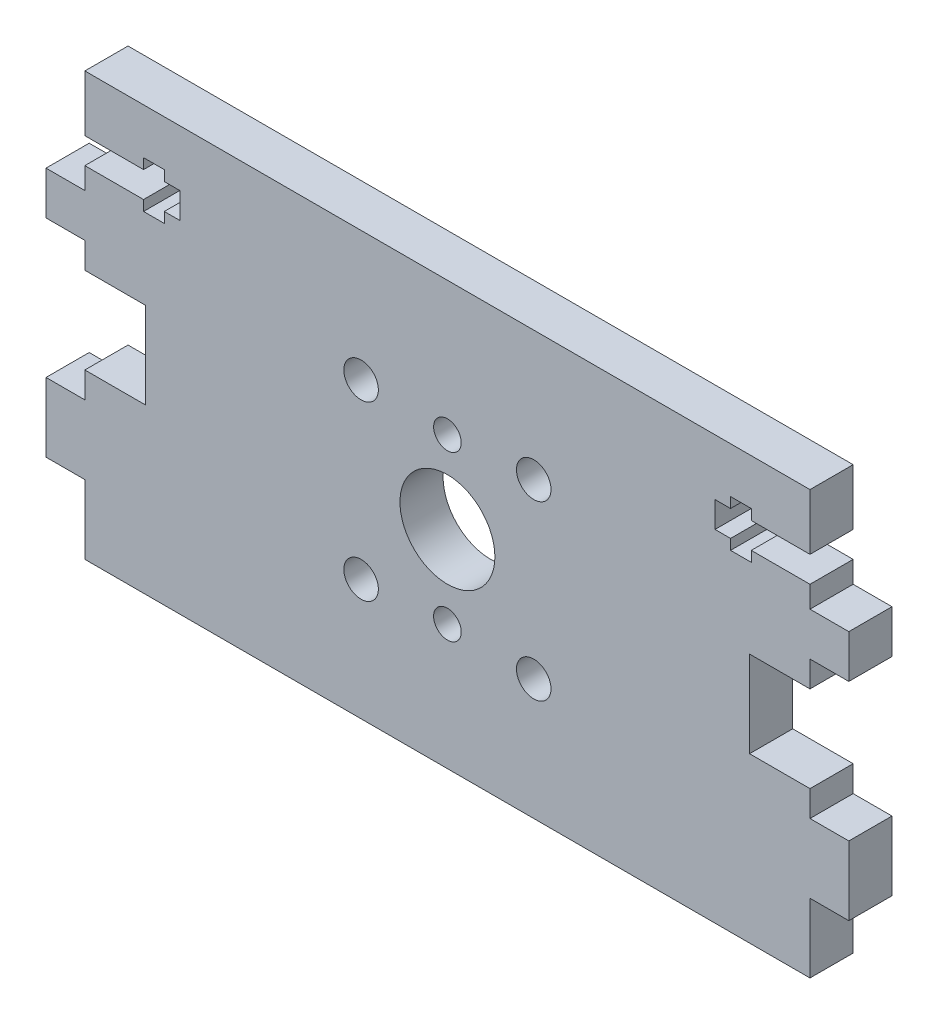
SolidWorks part; units mm, degrees
ref_plane "Plano frontal" through (0, 0, 0) normal (0, 0, 1) x (1, 0, 0)
ref_plane "Plano superior" through (0, 0, 0) normal (0, 1, 0) x (1, 0, 0)
ref_plane "Plano direito" through (0, 0, 0) normal (1, 0, 0) x (0, 0, -1)
sketch "Model" plane through (0, 0, 0) normal (0, 0, 1) x (1, 0, 0)
  line L0 (-6.2, 114.7) -> (-6.2, 113.5)
  line L1 (-6.2, 113.5) -> (-8, 113.5)
  line L2 (-8, 113.5) -> (-8, 110.5)
  line L3 (-8, 110.5) -> (-6.2, 110.5)
  line L4 (-6.2, 110.5) -> (-6.2, 109.3)
  line L5 (-6.2, 109.3) -> (-3.8, 109.3)
  line L6 (-3.8, 109.3) -> (-3.8, 110.5)
  line L7 (-3.8, 110.5) -> (3, 110.5)
  line L8 (3, 110.5) -> (3, 108)
  line L9 (3, 108) -> (7.5, 108)
  line L10 (7.5, 108) -> (7.5, 103)
  line L11 (7.5, 103) -> (3, 103)
  line L12 (3, 103) -> (3, 100)
  line L13 (3, 100) -> (-4, 100)
  line L14 (-4, 100) -> (-4, 90)
  line L15 (-4, 90) -> (3, 90)
  line L16 (3, 90) -> (3, 87)
  line L17 (3, 87) -> (7.5, 87)
  line L18 (7.5, 87) -> (7.5, 79)
  line L19 (7.5, 79) -> (3, 79)
  line L20 (3, 79) -> (3, 71)
  line L21 (3, 71) -> (-81, 71)
  line L22 (-81, 71) -> (-81, 79)
  line L23 (-81, 79) -> (-85.5, 79)
  line L24 (-85.5, 79) -> (-85.5, 87)
  line L25 (-85.5, 87) -> (-81, 87)
  line L26 (-81, 87) -> (-81, 90)
  line L27 (-81, 90) -> (-74, 90)
  line L28 (-74, 90) -> (-74, 100)
  line L29 (-74, 100) -> (-81, 100)
  line L30 (-81, 100) -> (-81, 103)
  line L31 (-81, 103) -> (-85.5, 103)
  line L32 (-85.5, 103) -> (-85.5, 108)
  line L33 (-85.5, 108) -> (-81, 108)
  line L34 (-81, 108) -> (-81, 110.5)
  line L35 (-81, 110.5) -> (-74.2, 110.5)
  line L36 (-74.2, 110.5) -> (-74.2, 109.3)
  line L37 (-74.2, 109.3) -> (-71.8, 109.3)
  line L38 (-71.8, 109.3) -> (-71.8, 110.5)
  line L39 (-71.8, 110.5) -> (-70, 110.5)
  line L40 (-70, 110.5) -> (-70, 113.5)
  line L41 (-70, 113.5) -> (-71.8, 113.5)
  line L42 (-71.8, 113.5) -> (-71.8, 114.7)
  line L43 (-71.8, 114.7) -> (-74.2, 114.7)
  line L44 (-74.2, 114.7) -> (-74.2, 113.5)
  line L45 (-74.2, 113.5) -> (-81, 113.5)
  line L46 (-81, 113.5) -> (-81, 120)
  line L47 (-81, 120) -> (3, 120)
  line L48 (3, 120) -> (3, 113.5)
  line L49 (3, 113.5) -> (-3.8, 113.5)
  line L50 (-3.8, 113.5) -> (-3.8, 114.7)
  line L51 (-3.8, 114.7) -> (-6.2, 114.7)
  circle A0 centre (-39, 85.5) radius 1.6
  circle A1 centre (-29, 105) radius 2
  circle A2 centre (-39, 104.5) radius 1.6
  circle A3 centre (-49, 85) radius 2
  circle A4 centre (-49, 105) radius 2
  circle A5 centre (-39, 95) radius 5.5
  circle A6 centre (-29, 85) radius 2
extrude "Ressalto-extrusão1" add sketch "Model" along normal blind 5
